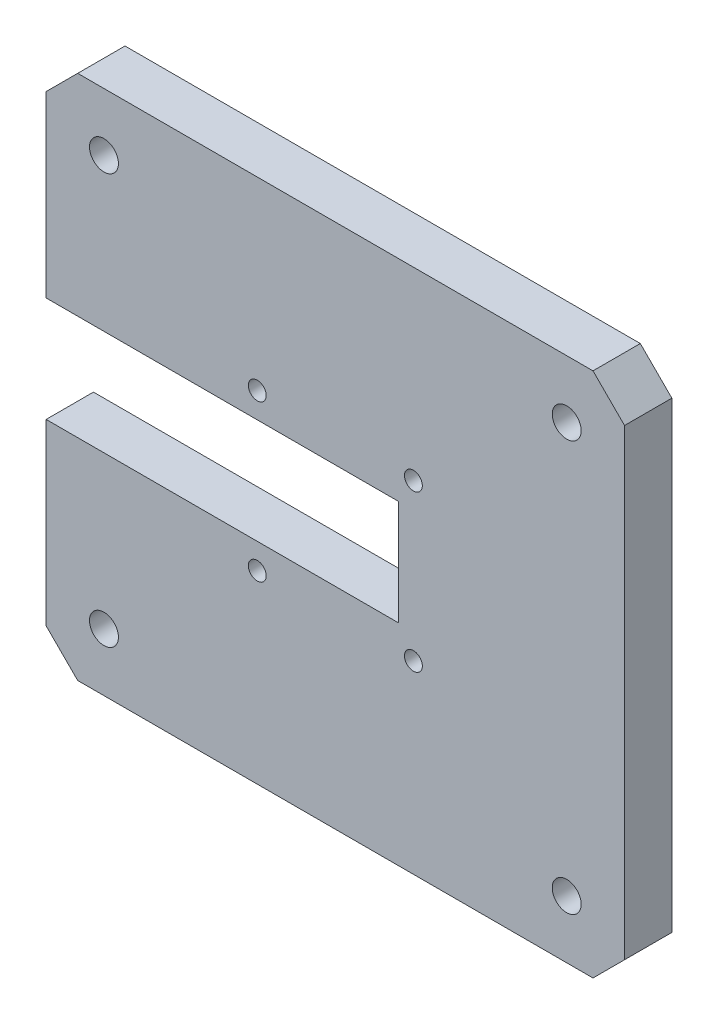
SolidWorks part; units mm, degrees
ref_plane "前视基准面" through (0, 0, 0) normal (0, 0, 1) x (1, 0, 0)
ref_plane "上视基准面" through (0, 0, 0) normal (0, 1, 0) x (1, 0, 0)
ref_plane "右视基准面" through (0, 0, 0) normal (1, 0, 0) x (0, 0, -1)
other "Configuration Table"
sketch "草图1" plane through (0, 0, 0) normal (0, 0, 1) x (1, 0, 0)
  line L0 (-55, -44) -> (-49, -50)
  line L1 (-49, -50) -> (49, -50)
  line L2 (49, -50) -> (55, -44)
  line L3 (55, -44) -> (55, 44)
  line L4 (55, 44) -> (49, 50)
  line L5 (49, 50) -> (-49, 50)
  line L6 (-49, 50) -> (-55, 44)
  line L7 (-55, 44) -> (-55, 10)
  line L8 (-55, 10) -> (12, 10)
  line L9 (12, 10) -> (12, -10)
  line L10 (12, -10) -> (-55, -10)
  line L11 (-55, -10) -> (-55, -44)
  circle A0 centre (-14.845, -14.845) radius 3.75
  circle A1 centre (-14.845, 14.845) radius 3.75
  circle A2 centre (14.845, -14.845) radius 3.75
  circle A3 centre (14.845, 14.845) radius 3.75
  circle A4 centre (-44, -39) radius 2.75
  circle A5 centre (-44, 39) radius 2.75
  circle A6 centre (44, -39) radius 2.75
  circle A7 centre (44, 39) radius 2.75
extrude "底层与螺钉头避空" add sketch "草图1" along normal blind 4 from offset 0
sketch "草图2" plane through (0, 0, 0) normal (0, 0, 1) x (1, 0, 0)
  line L0 (-55, -44) -> (-49, -50)
  line L1 (-49, -50) -> (49, -50)
  line L2 (49, -50) -> (55, -44)
  line L3 (55, -44) -> (55, 44)
  line L4 (55, 44) -> (49, 50)
  line L5 (49, 50) -> (-49, 50)
  line L6 (-49, 50) -> (-55, 44)
  line L7 (-55, 44) -> (-55, 10)
  line L8 (-55, 10) -> (12, 10)
  line L9 (12, 10) -> (12, -10)
  line L10 (12, -10) -> (-55, -10)
  line L11 (-55, -10) -> (-55, -44)
  circle A0 centre (-14.845, -14.845) radius 1.7
  circle A1 centre (-14.845, 14.845) radius 1.7
  circle A2 centre (14.845, -14.845) radius 1.7
  circle A3 centre (14.845, 14.845) radius 1.7
  circle A4 centre (-44, -39) radius 2.75
  circle A5 centre (-44, 39) radius 2.75
  circle A6 centre (44, -39) radius 2.75
  circle A7 centre (44, 39) radius 2.75
extrude "上层与通孔" add sketch "草图2" along normal blind 5 from offset 4
